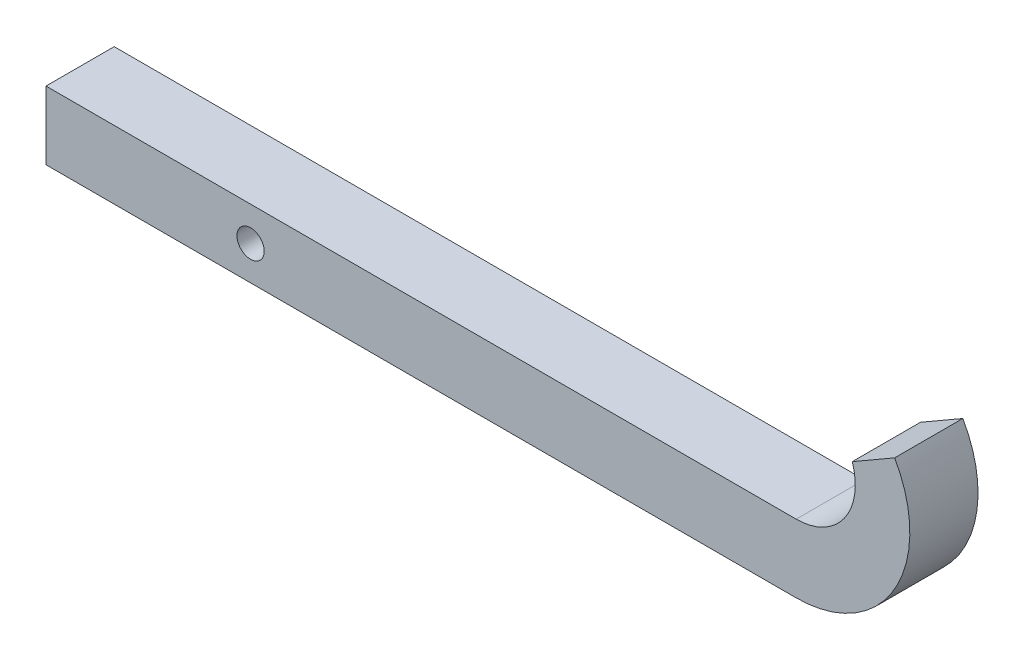
SolidWorks part; units mm, degrees
ref_plane "Alzado" through (0, 0, 0) normal (0, 0, 1) x (1, 0, 0)
ref_plane "Planta" through (0, 0, 0) normal (0, 1, 0) x (1, 0, 0)
ref_plane "Vista lateral" through (0, 0, 0) normal (1, 0, 0) x (0, 0, -1)
sketch "Croquis1" plane through (0, 0, 0) normal (0, 0, 1) x (1, 0, 0)
  line L0 (12.3302, 32.1189) -> (21.6506, 37.5)
  line L1 (0, 0) -> (-165, 0)
  line L3 (0, 15) -> (-165, 15)
  line L4 (-165, 0) -> (-165, 15)
  line L5 (0, 25) -> (12.3302, 32.1189) construction
  arc A0 (0, 15) -> (12.3302, 32.1189) centre (0, 28) ccw
  arc A1 (0, 0) -> (21.6506, 37.5) centre (0, 25) ccw
  dimension "D3" = 13
  dimension "D4" = 25
  dimension "D1" = 15
  dimension "D2" = 165
  dimension "D5" = 30
extrude "Saliente-Extruir1" add sketch "Croquis1" along normal mid plane 15
sketch "Croquis2" plane through (0, 0, 7.5) normal (0, 0, 1) x (1, 0, 0)
  line L0 (-165, 15) -> (-165, 0) construction
  circle A0 centre (-120, 7.5) radius 3
  point P5 (-165, 7.5)
  dimension "D1" = 6
  dimension "D2" = 120
extrude "Cortar-Extruir1" cut sketch "Croquis2" against normal through all
